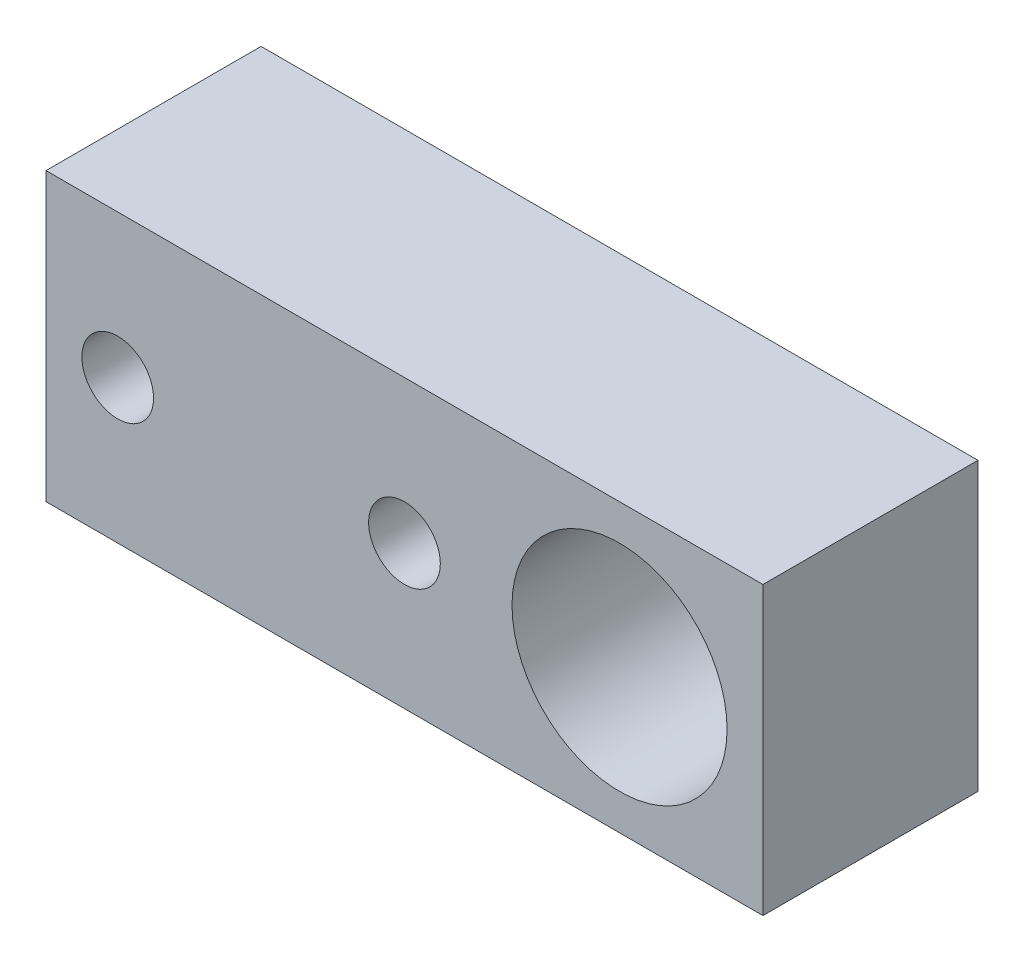
SolidWorks part; units mm, degrees
ref_plane "Front Plane" through (0, 0, 0) normal (0, 0, 1) x (1, 0, 0)
ref_plane "Top Plane" through (0, 0, 0) normal (0, 1, 0) x (1, 0, 0)
ref_plane "Right Plane" through (0, 0, 0) normal (1, 0, 0) x (0, 0, -1)
sketch "Sketch1" plane through (0, 0, 0) normal (1, 0, 0) x (0, 0, -1)
  line L1 (-7.5, -10) -> (7.5, -10)
  line L2 (-7.5, -10) -> (-7.5, 10)
  line L3 (-7.5, 10) -> (7.5, 10)
  line L4 (7.5, -10) -> (7.5, 10)
  line L5 (-7.5, -10) -> (7.5, 10) construction
  line L6 (-7.5, 10) -> (7.5, -10) construction
  point P0 (0, 0)
  dimension "D1" = 20
  dimension "D2" = 15
extrude "Boss-Extrude1" add sketch "Sketch1" along normal mid plane 50
sketch "Sketch2" plane through (0, 0, 7.5) normal (0, 0, 1) x (1, 0, 0)
  line L0 (0, 0) -> (15, 0) construction
  circle A0 centre (15, 0) radius 7.5
  dimension "D1" = 15
  dimension "D2" = 15
extrude "Cut-Extrude1" cut sketch "Sketch2" against normal through all and the other way through all
hole_wizard "M6 Tapped Hole1" positions "Sketch3" profile "Sketch4" tap size "M6" standard "ISO" end condition through all
sketch "Sketch3" plane through (0, 0, 7.5) normal (0, 0, 1) x (1, 0, 0)
  line L0 (-20, 0) -> (0, 0) construction
  point P0 (0, 0)
  point P3 (-20, 0)
  dimension "D1" = 20
sketch "Sketch4" plane through (0, 0, 7.5) normal (1, 0, 0) x (0, -1, 0)
  line L0 (0, 0) -> (0, 15)
  line L1 (0, 15) -> (2.5, 15)
  line L2 (2.5, 15) -> (2.5, 0)
  line L5 (2.5, 0) -> (0, 0)
  line L11 (0, -6.35) -> (0, 107.95) construction
  dimension "Thru Tap Drill Dia." = 5
  dimension "Thru Tap Drill Depth" = 15
cosmetic thread "Hole Thread1" parameters "D2"=6
cosmetic thread "Hole Thread2" parameters "D2"=6
